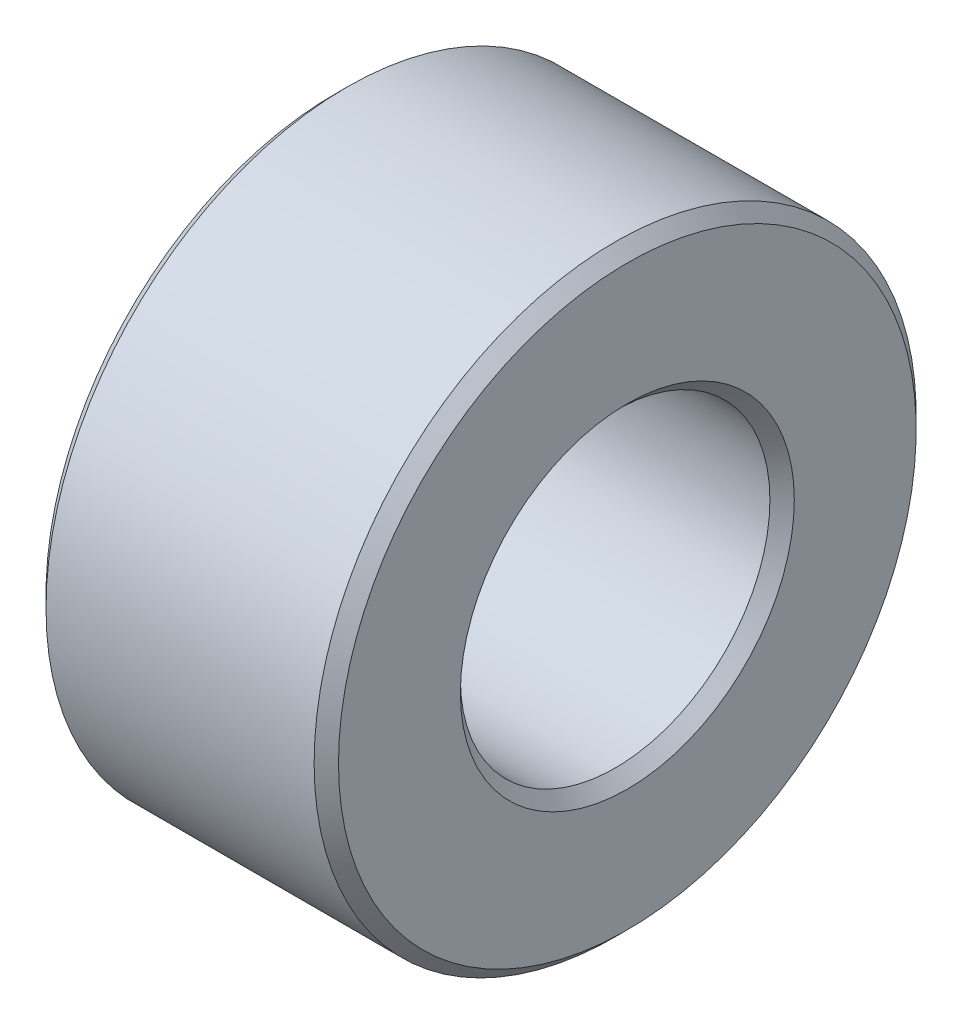
SolidWorks part; units mm, degrees
material "Alloy Steel"
ref_plane "Front Plane" through (0, 0, 0) normal (0, 0, 1) x (1, 0, 0)
ref_plane "Top Plane" through (0, 0, 0) normal (0, 1, 0) x (1, 0, 0)
ref_plane "Right Plane" through (0, 0, 0) normal (1, 0, 0) x (0, 0, -1)
sketch "Sketch1" plane through (0, 0, 0) normal (0, 0, 1) x (1, 0, 0)
  line L0 (0, 0) -> (3.9865, 0) construction
  line L1 (-3, 3.175) -> (3, 3.175)
  line L2 (-3, 3.175) -> (-3, 6.175)
  line L3 (-3, 6.175) -> (3, 6.175)
  line L4 (3, 6.175) -> (3, 3.175)
  line L5 (0, 0) -> (0, 3.7232) construction
  dimension "D1" = 3.175
  dimension "D2" = 3
  dimension "D3" = 6
revolve "Revolve1" add sketch "Sketch1" angle 360 about L0
chamfer "Chamfer1" distance 0.25 angle 45 4 edges at (-3, 0, 6.175) (-3, 0, 3.175) (3, 0, 6.175) (3, 0, 3.175)
